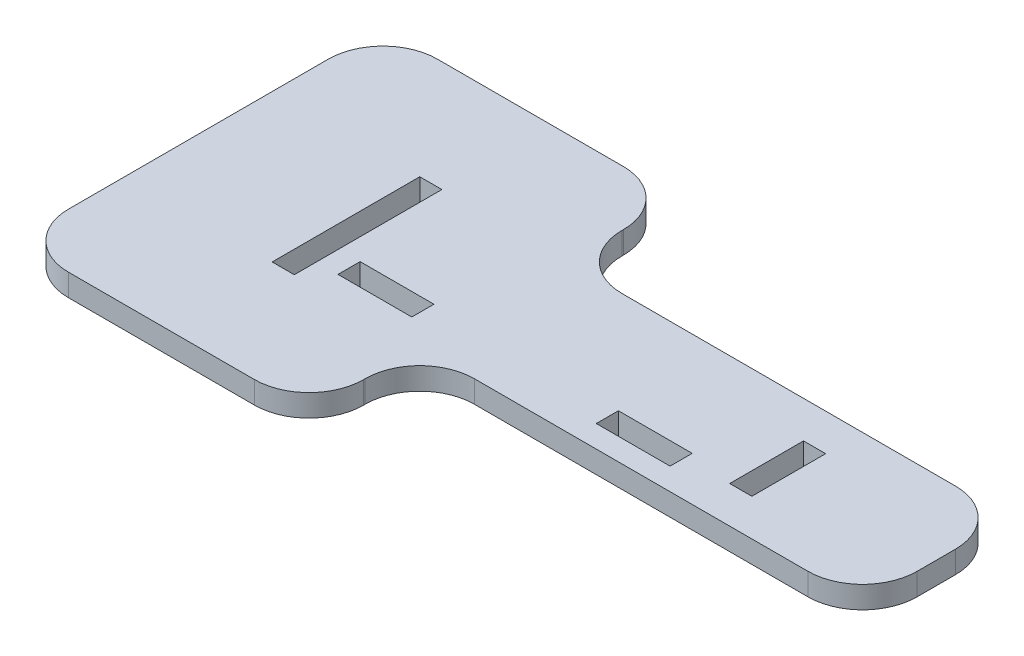
SolidWorks part; units mm, degrees
ref_plane "Front Plane" through (0, 0, 0) normal (0, 0, 1) x (1, 0, 0)
ref_plane "Top Plane" through (0, 0, 0) normal (0, 1, 0) x (1, 0, 0)
ref_plane "Right Plane" through (0, 0, 0) normal (1, 0, 0) x (0, 0, -1)
sketch "Sketch1" plane through (0, 0, 0) normal (0, 1, 0) x (1, 0, 0)
  line L1 (0, 0) -> (100, 0)
  line L2 (0, 0) -> (0, 50)
  line L3 (0, 50) -> (100, 50)
  line L4 (100, 0) -> (100, 50)
  dimension "D1" = 100
  dimension "D2" = 50
extrude "Boss-Extrude1" add sketch "Sketch1" along normal blind 3
sketch "Sketch2" plane through (0, 3, 0) normal (0, 1, 0) x (1, 0, 0)
  line L1 (100, 0) -> (40, 0)
  line L2 (100, 0) -> (100, 15)
  line L3 (100, 15) -> (40, 15)
  line L4 (40, 0) -> (40, 15)
  line L5 (100, 50) -> (40, 50)
  line L6 (100, 50) -> (100, 35)
  line L7 (100, 35) -> (40, 35)
  line L8 (40, 50) -> (40, 35)
  dimension "D1" = 60
  dimension "D2" = 15
extrude "Cut-Extrude1" cut sketch "Sketch2" against normal blind 3
fillet "Fillet1" radius 7.4 8 edges at (0, 1.5, -50) (0, 1.5, 0) (100, 1.5, -35) (100, 1.5, -15) (40, 1.5, -35) (40, 1.5, -50) (40, 1.5, 0) (40, 1.5, -15)
sketch "Sketch3" plane through (0, 0, 0) normal (0, -1, 0) x (1, 0, 0)
  line L1 (20, -15) -> (23, -15)
  line L2 (20, -15) -> (20, -35)
  line L3 (20, -35) -> (23, -35)
  line L4 (23, -15) -> (23, -35)
  line L5 (77, -20) -> (80, -20)
  line L6 (77, -20) -> (77, -30)
  line L7 (77, -30) -> (80, -30)
  line L8 (80, -20) -> (80, -30)
extrude "Cut-Extrude2" cut sketch "Sketch3" against normal blind 10
sketch "Sketch4" plane through (0, 0, 0) normal (0, -1, 0) x (1, 0, 0)
  line L1 (25.9197, -18) -> (35.9197, -18)
  line L2 (25.9197, -18) -> (25.9197, -21)
  line L3 (25.9197, -21) -> (35.9197, -21)
  line L4 (35.9197, -18) -> (35.9197, -21)
  line L5 (60.9197, -18) -> (70.9197, -18)
  line L6 (60.9197, -18) -> (60.9197, -21)
  line L7 (60.9197, -21) -> (70.9197, -21)
  line L8 (70.9197, -18) -> (70.9197, -21)
extrude "Cut-Extrude3" cut sketch "Sketch4" against normal blind 3
